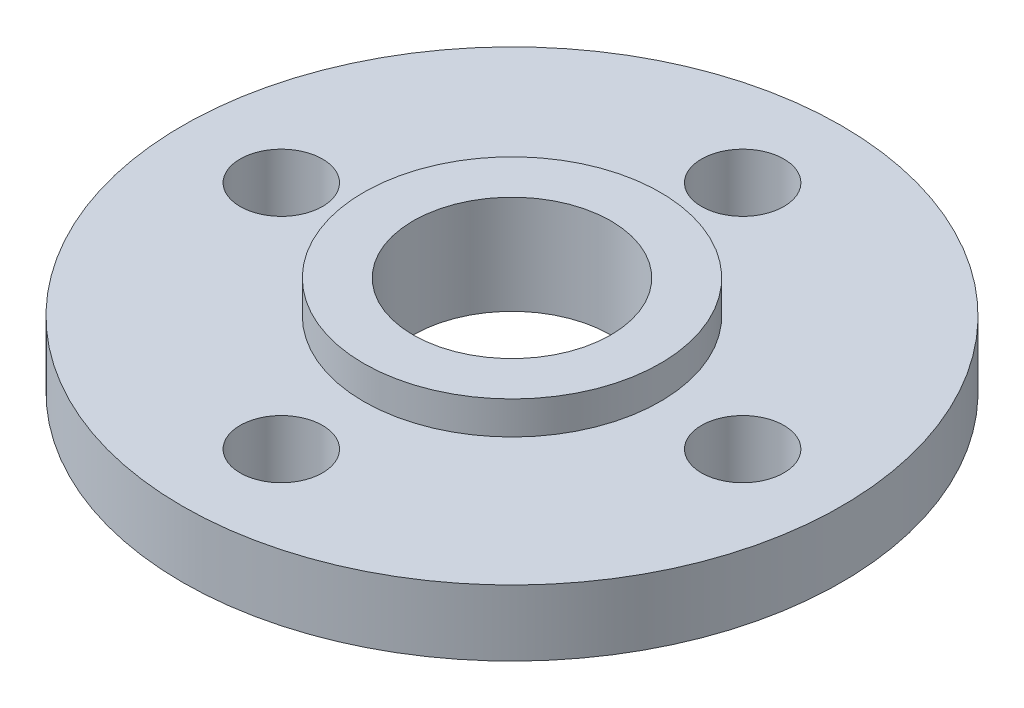
SolidWorks part; units mm, degrees
ref_plane "Спереди" through (0, 0, 0) normal (0, 0, 1) x (1, 0, 0)
ref_plane "Сверху" through (0, 0, 0) normal (0, 1, 0) x (1, 0, 0)
ref_plane "Справа" through (0, 0, 0) normal (1, 0, 0) x (0, 0, -1)
sketch "Эскиз1" plane through (0, 0, 0) normal (0, 1, 0) x (1, 0, 0)
  line L0 (0, 0) -> (7, 0) construction
  line L1 (0, 0) -> (0, -7) construction
  line L2 (0, 0) -> (-7, 0) construction
  line L3 (0, 0) -> (0, 7) construction
  circle A0 centre (0, 0) radius 10
  circle A1 centre (7, 0) radius 1.25
  circle A2 centre (0, 0) radius 3
  circle A3 centre (0, -7) radius 1.25
  circle A4 centre (-7, 0) radius 1.25
  circle A5 centre (0, 7) radius 1.25
  point P15 (0, 0)
  dimension "D1" = 4
extrude "Бобышка-Вытянуть1" add sketch "Эскиз1" along normal blind 2
sketch "Эскиз2" plane through (0, 2, 0) normal (0, 1, 0) x (1, 0, 0)
  circle A0 centre (0, 0) radius 3
  circle A1 centre (0, 0) radius 4.5
extrude "Бобышка-Вытянуть2" add sketch "Эскиз2" along normal blind 1
